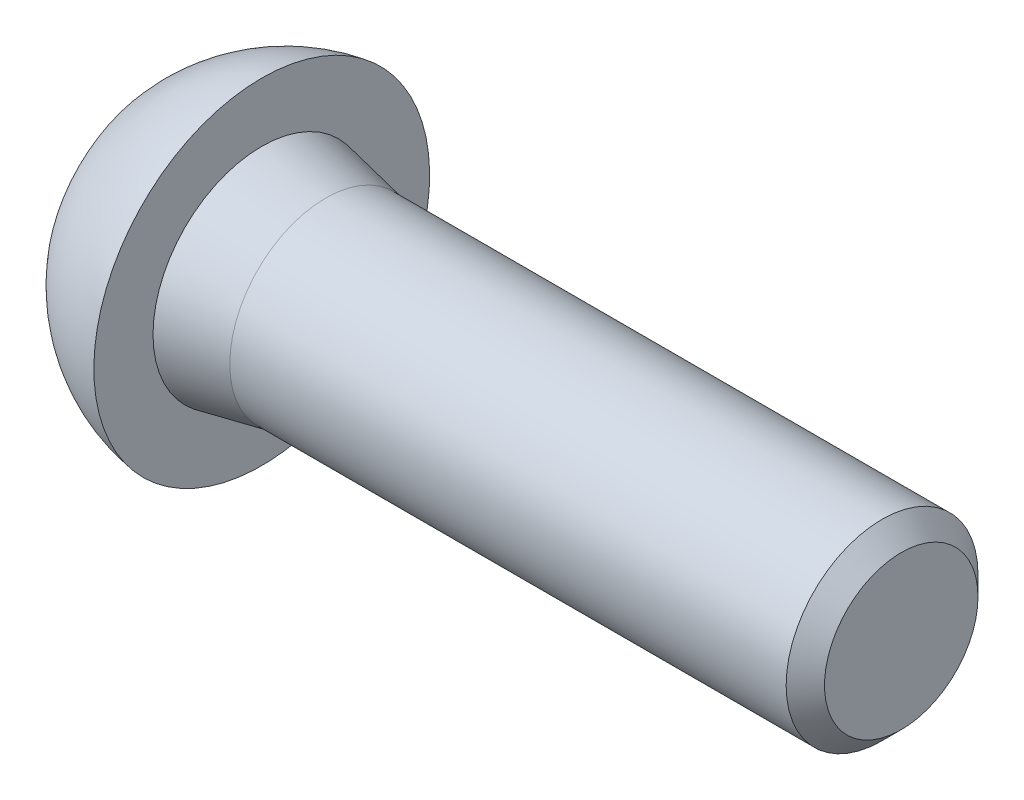
SolidWorks part; units mm, degrees
ref_plane "前视基准面" through (0, 0, 0) normal (0, 0, 1) x (1, 0, 0)
ref_plane "上视基准面" through (0, 0, 0) normal (0, 1, 0) x (1, 0, 0)
ref_plane "右视基准面" through (0, 0, 0) normal (1, 0, 0) x (0, 0, -1)
sketch "草图1" plane through (0, 0, 0) normal (0, 0, 1) x (1, 0, 0)
  line L0 (0, 0) -> (0, 3)
  line L1 (0, 3) -> (-18, 3)
  line L2 (-18, 3) -> (-20, 3.4)
  line L3 (-20, 3.4) -> (-20, 5.25)
  line L4 (0, 0) -> (-23.3, 0)
  line L5 (0, 0) -> (-159.9915, 0) construction
  line L6 (-23.3, 3.42) -> (-23.3, 0)
  arc A0 (-20, 5.25) -> (-23.3, 3.42) centre (-19.246, 0) ccw
  dimension "D2" = 20
  dimension "D1" = 6
  dimension "D3" = 6.8
  dimension "D4" = 10.5
  dimension "D5" = 2
  dimension "D6" = 6.84
  dimension "D7" = 3.3
revolve "旋转1" add sketch "草图1" angle 360 about L5
cosmetic thread "装饰螺纹线1" parameters "D2"=5.16
sketch "草图4" plane through (-23.3, 0, 0) normal (-1, 0, 0) x (0, 0, 1)
  line L1 (0, 2.3094) -> (-2, 1.1547)
  line L2 (-2, 1.1547) -> (-2, -1.1547)
  line L3 (-2, -1.1547) -> (0, -2.3094)
  line L4 (0, -2.3094) -> (2, -1.1547)
  line L5 (2, -1.1547) -> (2, 1.1547)
  line L6 (2, 1.1547) -> (0, 2.3094)
  circle A0 centre (0, 0) radius 2 construction
  dimension "D1" = 4
extrude "切除-拉伸1" cut sketch "草图4" against normal blind 2.08
chamfer "倒角1" distance 0.6 angle 45 1 edges at (0, 0, -3)
ref_plane "基准面2" through (-20.8075, 0, 0) normal (-1, 0, 0) x (0, 0, 1)
sketch "草图6" plane through (-21.22, 0, 0) normal (-1, 0, 0) x (0, 0, 1)
  line L1 (0, 2.3094) -> (-2, 1.1547)
  line L2 (-2, 1.1547) -> (-2, -1.1547)
  line L3 (-2, -1.1547) -> (0, -2.3094)
  line L4 (0, -2.3094) -> (2, -1.1547)
  line L5 (2, -1.1547) -> (2, 1.1547)
  line L6 (2, 1.1547) -> (0, 2.3094)
  circle A0 centre (0, 0) radius 2 construction
sketch "草图7" plane through (-20.8075, 0, 0) normal (-1, 0, 0) x (0, 0, 1)
  point P0 (0, 0)
loft "切除-放样1" cut profiles "草图7", "草图6"
